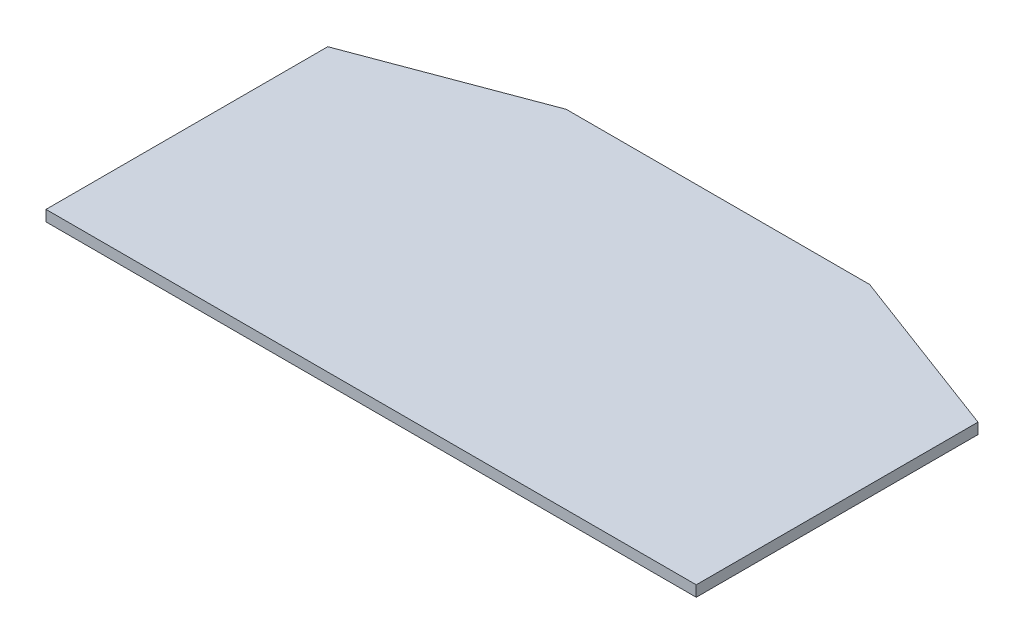
SolidWorks part; units mm, degrees
ref_plane "Front Plane" through (0, 0, 0) normal (0, 0, 1) x (1, 0, 0)
ref_plane "Top Plane" through (0, 0, 0) normal (0, 1, 0) x (1, 0, 0)
ref_plane "Right Plane" through (0, 0, 0) normal (1, 0, 0) x (0, 0, -1)
sketch "Sketch1" plane through (0, 0, 0) normal (0, 1, 0) x (1, 0, 0)
  line L0 (-92.9216, 89.0184) -> (669.0784, 89.0184)
  line L1 (669.0784, 89.0184) -> (669.0784, 419.2184)
  line L2 (-92.9216, 89.0184) -> (-92.9216, 419.2184)
  line L5 (110.2784, 495.4184) -> (465.8784, 495.4184)
  line L8 (110.2784, 495.4184) -> (-92.9216, 419.2184)
  line L9 (465.8784, 495.4184) -> (669.0784, 419.2184)
  line L10 (-92.9216, 495.4184) -> (669.0784, 495.4184) construction
extrude "Boss-Extrude1" add sketch "Sketch1" along normal blind 12.7
